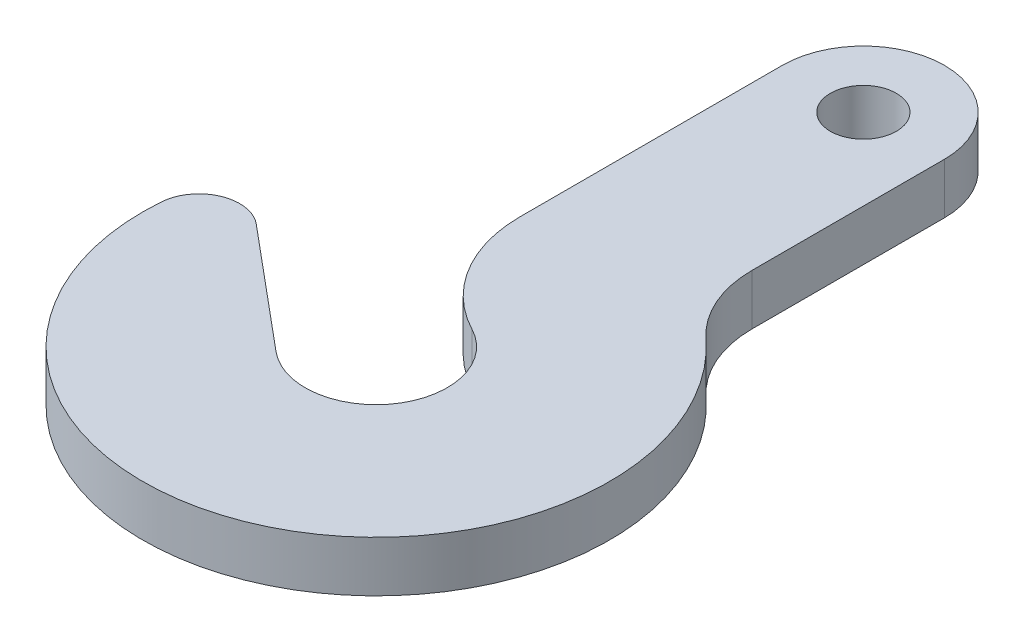
SolidWorks part; units mm, degrees
ref_plane "Front Plane" through (0, 0, 0) normal (0, 0, 1) x (1, 0, 0)
ref_plane "Top Plane" through (0, 0, 0) normal (0, 1, 0) x (1, 0, 0)
ref_plane "Right Plane" through (0, 0, 0) normal (1, 0, 0) x (0, 0, -1)
sketch "Sketch1" plane through (0, 0, 0) normal (0, 1, 0) x (1, 0, 0)
  line L0 (-54, 0) -> (-53.3039, 0) construction
  line L1 (0, -645.0443) -> (0, 645.0443) construction
  line L2 (0, 0) -> (0, 88)
  line L3 (-8, 0) -> (-8, 14) construction
  line L4 (16, 88) -> (16, 50.0799)
  line L5 (-16, 88) -> (-16, 36.3318)
  line L6 (-40.7524, 9.1257) -> (-16.9775, -10.7427)
  line L7 (-8, 0) -> (-8, 88) construction
  line L8 (-29.8324, 0) -> (31607.1722, 0) construction
  circle A0 centre (0, 88) radius 6.5
  arc A1 (16, 88) -> (-16, 88) centre (0, 88) ccw
  arc A2 (-53.8577, 3.6158) -> (23.1176, 33.8776) centre (-8, 0) ccw
  arc A3 (-16.9775, -10.7427) -> (-1.5122, 12.406) centre (-8, 0) ccw
  arc A4 (16, 50.0799) -> (23.1176, 33.8776) centre (38, 50.0799) ccw
  arc A5 (-16, 36.3318) -> (-1.5122, 12.406) centre (11, 36.3318) ccw
  arc A6 (-40.7524, 9.1257) -> (-53.8577, 3.6158) centre (-45.8824, 2.987) ccw
  point P8 (0, 0)
  point P23 (0, 0)
  point P26 (0, 0)
  point P28 (0, 0)
  point P29 (0, 0)
  dimension "D2" = 13
  dimension "D3" = 32
  dimension "D5" = 28
  dimension "D6" = 92
  dimension "D7" = 44
  dimension "D9" = 16
  dimension "D8" = 54
  dimension "D1" = 88
  dimension "D10" = 16.9775
  dimension "D4" = 8
extrude "Boss-Extrude1" add sketch "Sketch1" along normal blind 10
